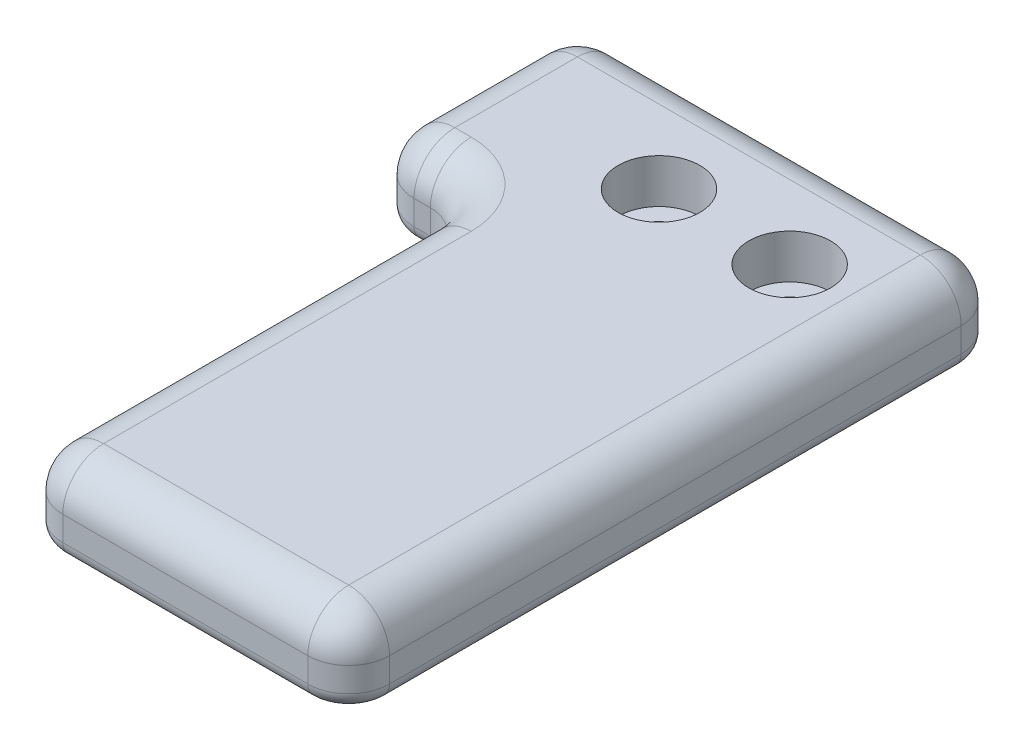
SolidWorks part; units mm, degrees
ref_plane "Alzado" through (0, 0, 0) normal (0, 0, 1) x (1, 0, 0)
ref_plane "Planta" through (0, 0, 0) normal (0, 1, 0) x (1, 0, 0)
ref_plane "Vista lateral" through (0, 0, 0) normal (1, 0, 0) x (0, 0, -1)
sketch "Croquis1" plane through (0, 0, 0) normal (0, 1, 0) x (1, 0, 0)
  line L0 (27.7976, -8) -> (27.7976, 47)
  line L1 (27.7976, -8) -> (67.7976, -8)
  line L2 (15.7976, 72) -> (67.7976, 72)
  line L3 (67.7976, -8) -> (67.7976, 72)
  line L4 (-60, 72) -> (90, 72) construction
  line L7 (27.7976, 47) -> (15.7976, 47)
  line L8 (15.7976, 47) -> (15.7976, 72)
  dimension "D1" = 40
  dimension "D2" = 52
  dimension "D3" = 80
  dimension "D4" = 25
extrude "Saliente-Extruir1" add sketch "Croquis1" along normal blind 10
fillet "Redondeo2" radius 5 6 edges at (67.7976, 5, 8) (27.7976, 5, 8) (67.7976, 5, -72) (15.7976, 5, -72) (27.7976, 5, -47) (15.7976, 5, -47)
fillet "Redondeo3" radius 5 12 edges at (27.7976, 10, -19.5) (47.7976, 10, 8) (67.7976, 10, -32) (66.3331, 10, 6.5355) (29.262, 10, 6.5355) (41.7976, 10, -72) (66.3331, 10, -70.5355) (17.262, 10, -70.5355) (15.7976, 10, -59.5) (17.262, 10, -48.4645) (26.3331, 10, -45.5355) (21.7976, 10, -47)
fillet "Redondeo5" radius 2 12 edges at (41.7976, 0, -72) (27.7976, 0, -19.5) (47.7976, 0, 8) (67.7976, 0, -32) (29.262, 0, 6.5355) (66.3331, 0, 6.5355) (66.3331, 0, -70.5355) (15.7976, 0, -59.5) (21.7976, 0, -47) (17.262, 0, -70.5355) (17.262, 0, -48.4645) (26.3331, 0, -45.5355)
hole_wizard "Taladro roscado M51" positions "Croquis3" profile "Croquis2" counterbore size "M5" standard "Iso" end condition through all
sketch "Croquis3" plane through (-0.509, 10, 14.9676) normal (0, -1, 0) x (-1, 0, 0)
  line L0 (-68.3065, 11.9676) -> (-68.3065, 81.9676) construction
  line L1 (59.491, 86.9676) -> (-90.509, 86.9676) construction
  line L2 (-63.3065, 86.9676) -> (-21.3065, 86.9676) construction
  line L3 (-28.3065, 56.9676) -> (-28.3065, 11.9676) construction
  point P0 (-56.3065, 72.9676)
  point P2 (-40.3065, 72.9676)
  dimension "D1" = 12
  dimension "D2" = 14
  dimension "D3" = 14
  dimension "D4" = 12
sketch "Croquis2" plane through (55.7976, 10, -58) normal (1, 0, 0) x (0, 0, 1)
  line L0 (0, 0) -> (0, 10)
  line L1 (0, 10) -> (2.75, 10)
  line L3 (2.75, 10) -> (2.75, 5.4)
  line L4 (2.75, 5.4) -> (5, 5.4)
  line L5 (5, 5.4) -> (5, 0)
  line L7 (5, 0) -> (0, 0)
  line L11 (0, -6.35) -> (0, 107.95) construction
  dimension "Diámetro de taladro hasta el siguiente" = 5.5
  dimension "Profundidad de taladro hasta el siguiente" = 10
  dimension "Diámetro de refrentado" = 10
  dimension "Profundidad de refrentado" = 5.4
